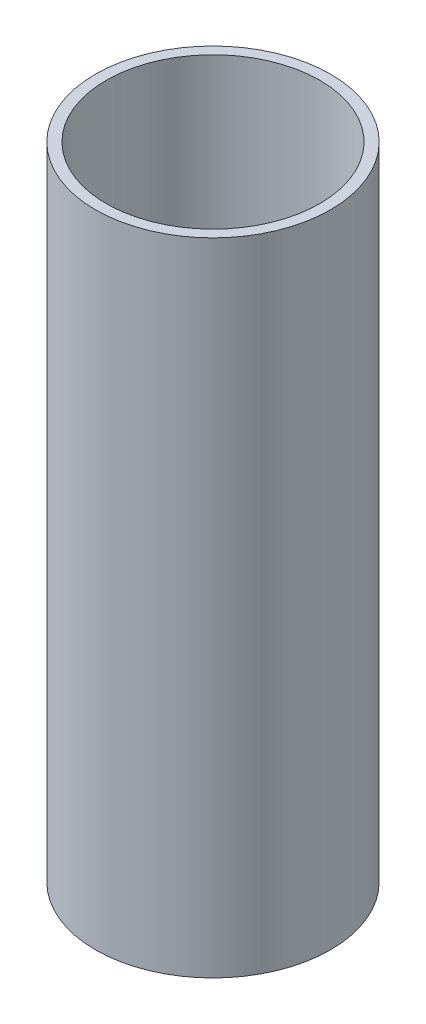
SolidWorks part; units mm, degrees
ref_plane "Front Plane" through (0, 0, 0) normal (0, 0, 1) x (1, 0, 0)
ref_plane "Top Plane" through (0, 0, 0) normal (0, 1, 0) x (1, 0, 0)
ref_plane "Right Plane" through (0, 0, 0) normal (1, 0, 0) x (0, 0, -1)
sketch "Sketch1" plane through (0, 0, 0) normal (0, 1, 0) x (1, 0, 0)
  circle A0 centre (0, 0) radius 12.7
  circle A1 centre (0, 0) radius 13.97
  dimension "D1" = 25.4
  dimension "D2" = 1.27
extrude "Boss-Extrude1" add sketch "Sketch1" along normal blind 76.2
